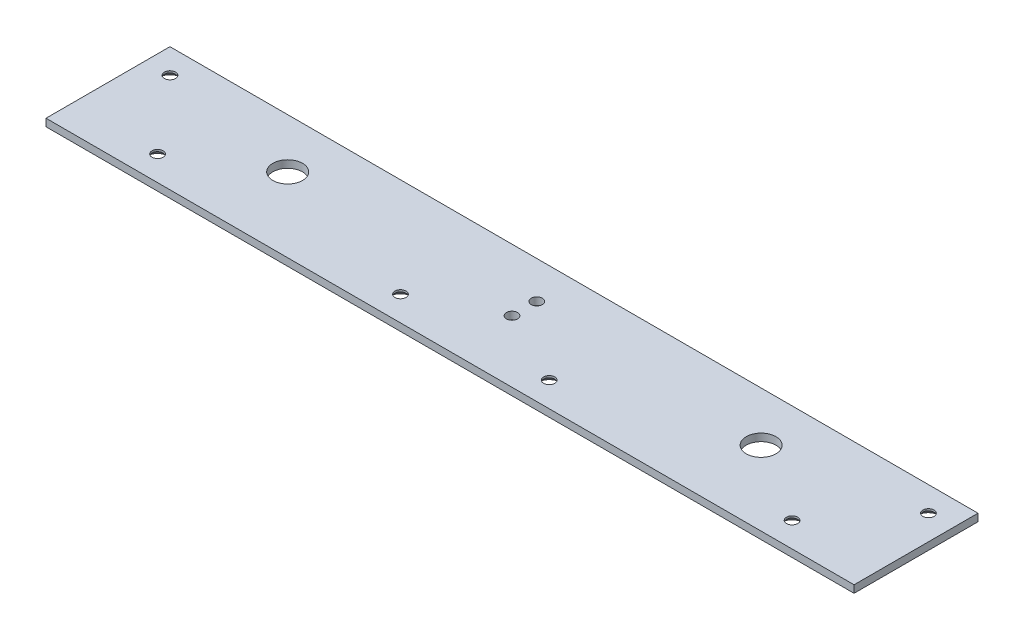
SolidWorks part; units mm, degrees
ref_plane "Ebene vorne" through (0, 0, 0) normal (0, 0, 1) x (1, 0, 0)
ref_plane "Ebene oben" through (0, 0, 0) normal (0, 1, 0) x (1, 0, 0)
ref_plane "Ebene rechts" through (0, 0, 0) normal (1, 0, 0) x (0, 0, -1)
sketch "Skizze1" plane through (0, 0, 0) normal (0, 1, 0) x (1, 0, 0)
  line L1 (-163, -25) -> (163, -25)
  line L2 (-163, -25) -> (-163, 25)
  line L3 (-163, 25) -> (163, 25)
  line L4 (163, -25) -> (163, 25)
  line L5 (-163, -25) -> (163, 25) construction
  line L6 (-163, 25) -> (163, -25) construction
  point P0 (0, 0)
  dimension "D1" = 50
  dimension "D2" = 326
extrude "Aufsatz-Linear austragen1" add sketch "Skizze1" along normal blind 3
hole_wizard "Durchgangsloch für M41" positions "Skizze2" profile "Skizze3" hole size "M4" standard "DIN" end condition up to next
sketch "Skizze2" plane through (0, 3, 0) normal (0, 1, 0) x (1, 0, 0)
  line L0 (-163, -25) -> (163, -25) construction
  point P0 (0, 0)
  point P2 (0, 10)
  dimension "D1" = 10
  dimension "D2" = 25
sketch "Skizze3" plane through (0, 3, 0) normal (1, 0, 0) x (0, 0, 1)
  line L0 (0, 0) -> (0, 3)
  line L1 (0, 3) -> (2.25, 3)
  line L2 (2.25, 3) -> (2.25, 0)
  line L5 (2.25, 0) -> (0, 0)
  line L11 (0, -6.35) -> (0, 107.95) construction
  dimension "Bohrerdurchmesser" = 4.5
  dimension "Bohrungstiefe" = 3
hole_wizard "Ø9.0 (12) Durchmesser Bohrung1" positions "Skizze4" profile "Skizze5" hole size "Ø9.0" standard "ANSI Metric" end condition through all
sketch "Skizze4" plane through (0, 3, 0) normal (0, 1, 0) x (1, 0, 0)
  circle A0 centre (0, 0) radius 2.25 construction
  point P0 (-95.5, 5)
  point P2 (95.5, 5)
  dimension "D1" = 95.5
  dimension "D2" = 95.5
  dimension "D3" = 5
  dimension "D4" = 5
sketch "Skizze5" plane through (-95.5, 3, -5) normal (1, 0, 0) x (0, 0, 1)
  line L0 (0, 0) -> (0, 3)
  line L1 (0, 3) -> (6, 3)
  line L2 (6, 3) -> (6, 0)
  line L5 (6, 0) -> (0, 0)
  line L11 (0, -6.35) -> (0, 107.95) construction
  dimension "Bohrerdurchmesser" = 12
  dimension "Bohrungstiefe" = 3
hole_wizard "Formsenkung für M4 SFHCS1" positions "Skizze6" profile "Skizze7" countersink size "M4" standard "ANSI Metric" end condition through all
sketch "Skizze6" plane through (0, 0, 0) normal (0, -1, 0) x (-1, 0, 0)
  line L0 (-163, -25) -> (-163, 25) construction
  line L1 (163, 25) -> (163, -25) construction
  line L2 (-163, 25) -> (163, 25) construction
  line L3 (163, -25) -> (-163, -25) construction
  point P0 (-153, 15)
  point P2 (153, 15)
  point P4 (128, -15)
  point P6 (30, -15)
  point P8 (-30, -15)
  point P10 (-128, -15)
  dimension "D1" = 10
  dimension "D2" = 10
  dimension "D3" = 10
  dimension "D4" = 10
  dimension "D5" = 35
  dimension "D6" = 35
  dimension "D7" = 10
  dimension "D8" = 10
  dimension "D9" = 10
  dimension "D10" = 10
  dimension "D11" = 30
  dimension "D12" = 30
sketch "Skizze7" plane through (153, 0, -15) normal (1, 0, 0) x (0, 0, -1)
  line L0 (0, 0) -> (0, 3)
  line L1 (0, 3) -> (2.25, 3)
  line L2 (2.25, 3) -> (2.25, 2.23)
  line L3 (2.25, 2.23) -> (4.48, 0)
  line L5 (4.48, 0) -> (0, 0)
  line L6 (-2.25, 2.23) -> (-4.48, 0) construction
  line L11 (0, -6.35) -> (0, 107.95) construction
  dimension "Bohrerdurchmesser" = 4.5
  dimension "Bohrungstiefe" = 3
  dimension "Senkdurchmesser (Oben)" = 8.96
  dimension "Senkwinkel (Oben)" = 90
equation "\"D2@Skizze4\"=\"D1@Skizze4\""
